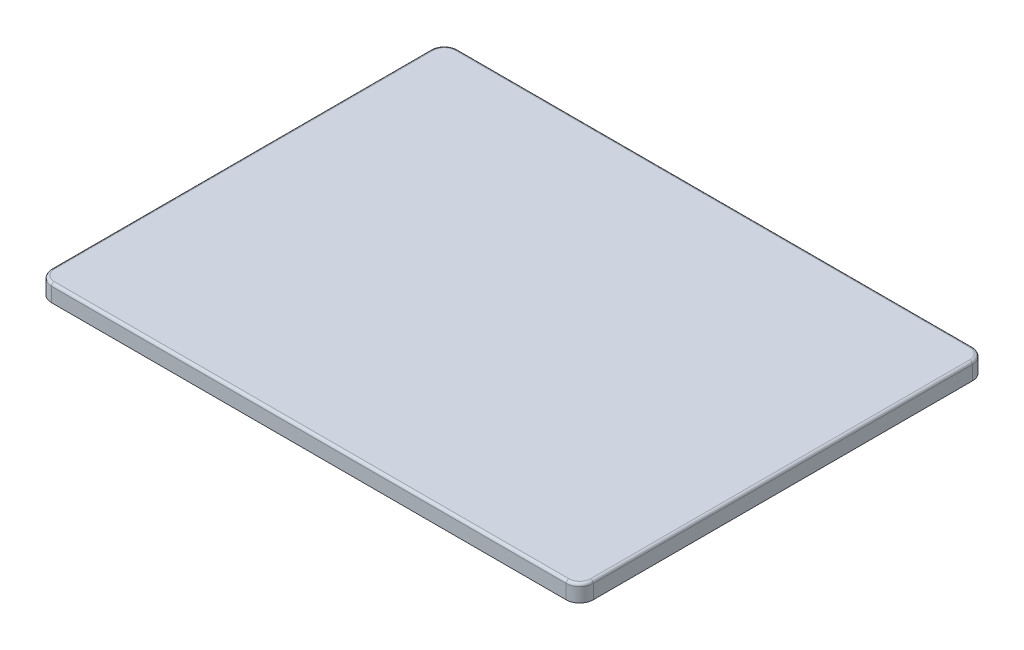
SolidWorks part; units mm, degrees
material "AISI Type 316L stainless steel"
ref_plane "Front Plane" through (0, 0, 0) normal (0, 0, 1) x (1, 0, 0)
ref_plane "Top Plane" through (0, 0, 0) normal (0, 1, 0) x (1, 0, 0)
ref_plane "Right Plane" through (0, 0, 0) normal (1, 0, 0) x (0, 0, -1)
sketch "Sketch1" plane through (0, 0, 0) normal (0, 1, 0) x (1, 0, 0)
  line L1 (-25.4, 19.05) -> (25.4, 19.05)
  line L2 (-25.4, 19.05) -> (-25.4, -19.05)
  line L3 (-25.4, -19.05) -> (25.4, -19.05)
  line L4 (25.4, 19.05) -> (25.4, -19.05)
  line L5 (-25.4, 19.05) -> (25.4, -19.05) construction
  line L6 (-25.4, -19.05) -> (25.4, 19.05) construction
  point P0 (0, 0)
  dimension "D1" = 50.8
  dimension "D2" = 38.1
extrude "Boss-Extrude1" add sketch "Sketch1" along normal blind 1.5875
fillet "Fillet1" radius 1.27 4 edges at (25.4, 0.7937, 19.05) (25.4, 0.7937, -19.05) (-25.4, 0.7937, -19.05) (-25.4, 0.7937, 19.05)
fillet "Fillet2" radius 0.254 8 edges at (-25.028, 1.5875, 18.678) (-25.4, 1.5875, 0) (-25.028, 1.5875, -18.678) (0, 1.5875, -19.05) (25.028, 1.5875, -18.678) (25.4, 1.5875, 0) (25.028, 1.5875, 18.678) (0, 1.5875, 19.05)
